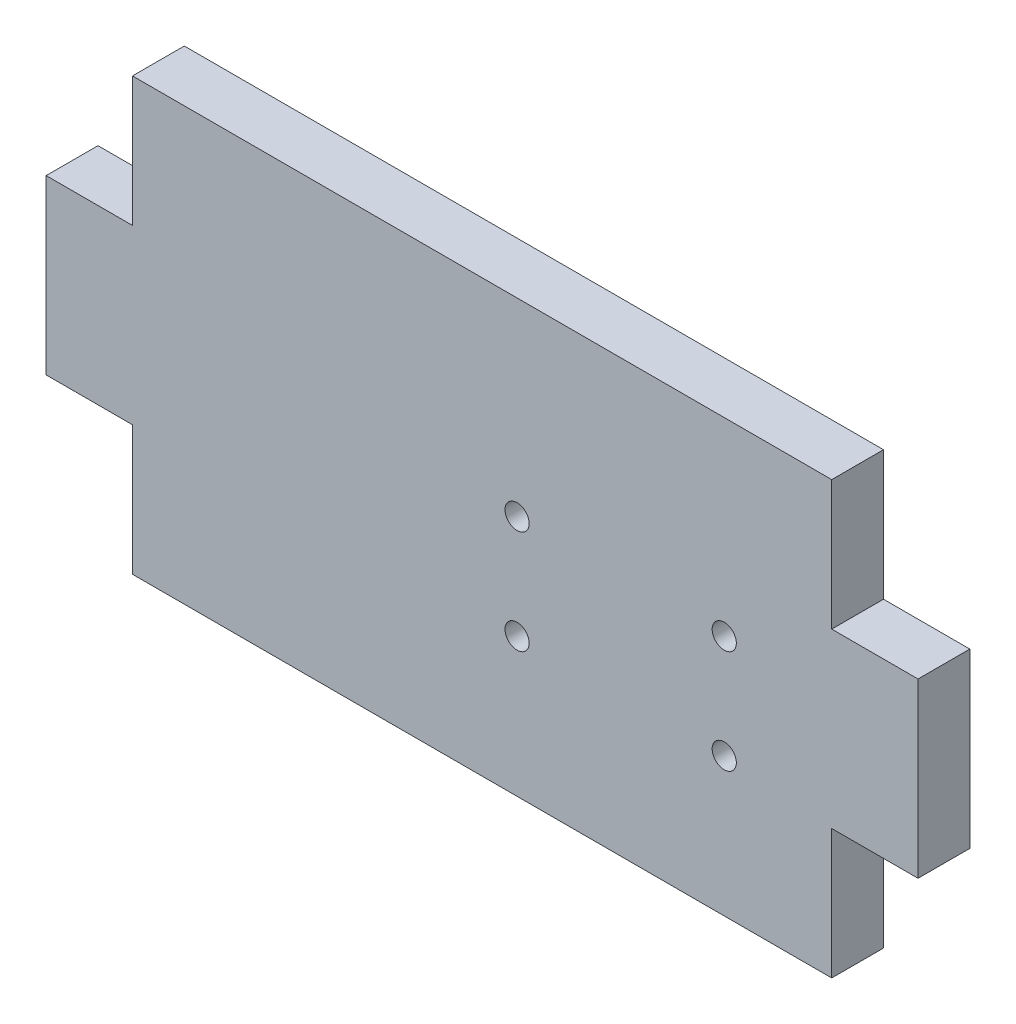
SolidWorks part; units mm, degrees
ref_plane "Plan de face" through (0, 0, 0) normal (0, 0, 1) x (1, 0, 0)
ref_plane "Plan de dessus" through (0, 0, 0) normal (0, 1, 0) x (1, 0, 0)
ref_plane "Plan de droite" through (0, 0, 0) normal (1, 0, 0) x (0, 0, -1)
sketch "Esquisse1" plane through (0, 0, 0) normal (0, 0, 1) x (1, 0, 0)
  line L1 (0, 0) -> (81, 0)
  line L2 (0, 0) -> (0, 50)
  line L3 (0, 50) -> (81, 50)
  line L4 (81, 0) -> (81, 50)
  line L5 (0, 35) -> (-10, 35)
  line L6 (0, 35) -> (0, 15)
  line L7 (0, 15) -> (-10, 15)
  line L8 (-10, 35) -> (-10, 15)
  line L9 (81, 35) -> (91, 35)
  line L10 (81, 35) -> (81, 15)
  line L11 (81, 15) -> (91, 15)
  line L12 (91, 35) -> (91, 15)
  point P13 (-10, 25)
  point P14 (0, 25)
  point P15 (91, 25)
  point P16 (81, 25)
  dimension "D1" = 81
  dimension "D2" = 50
  dimension "D3" = 10
  dimension "D4" = 20
  dimension "D5" = 10
  dimension "D6" = 20
extrude "Boss.-Extru.1" add sketch "Esquisse1" along normal blind 6 contours L5 L8 L7 L2 | L1 L4 L3 L2 | L12 L9 L4 L11
sketch "Esquisse2" plane through (0, 0, 0) normal (0, 0, -1) x (-1, 0, 0)
  circle A0 centre (-44.5503, 16.0653) radius 1.4
  circle A1 centre (-44.5503, 28.0653) radius 1.4
  circle A2 centre (-68.5503, 28.0653) radius 1.4
  circle A3 centre (-68.5503, 16.0653) radius 1.4
  dimension "D1" = 2.8
  dimension "D2" = 2.8
  dimension "D3" = 2.8
  dimension "D4" = 2.8
extrude "Enlèv. mat.-Extru.1" cut sketch "Esquisse2" against normal up to surface (6 mm away) up to face at (40.5, 25, 6)
sketch "Esquisse3" plane through (0, 0, 0) normal (0, 0, -1) x (-1, 0, 0)
  circle A0 centre (-68.5503, 28.0653) radius 3
  circle A1 centre (-44.5503, 28.0653) radius 3
  circle A2 centre (-44.5503, 16.0653) radius 3
  circle A3 centre (-68.5503, 16.0653) radius 3
  dimension "D1" = 6
extrude "Enlèv. mat.-Extru.2" cut sketch "Esquisse3" against normal blind 4
